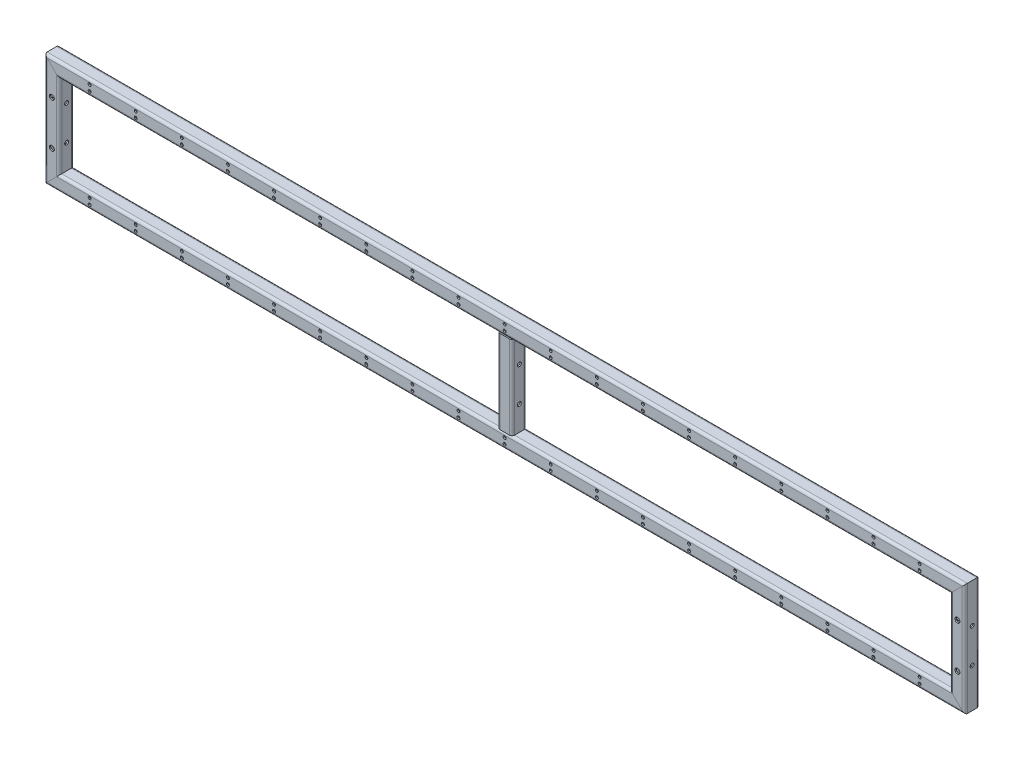
SolidWorks part; units mm, degrees
ref_plane "Front Plane" through (0, 0, 0) normal (0, 0, 1) x (1, 0, 0)
ref_plane "Top Plane" through (0, 0, 0) normal (0, 1, 0) x (1, 0, 0)
ref_plane "Right Plane" through (0, 0, 0) normal (1, 0, 0) x (0, 0, -1)
sketch "Sketch1" plane through (0, 0, 0) normal (0, 0, 1) x (1, 0, 0)
  line L0 (-1876, 15) -> (-1876, -10) construction
  line L1 (-15, -200) -> (-1861, -200)
  line L2 (-15, -200) -> (-15, -400)
  line L3 (-15, -400) -> (-1861, -400)
  line L4 (-1861, -200) -> (-1861, -400)
  line L6 (-938, -200) -> (-938, -400)
  line L7 (-37, -300) -> (-1897.553, -300) construction
  line L8 (-37, -589) -> (-37, -11) construction
  dimension "D1" = 15
  dimension "D2" = 15
  dimension "D3" = 200
  dimension "D4" = 100
other "Structural Member1"
ref_plane "Plane1" through (-1861, -200, 0) normal (0, -1, 0) x (1, 0, 0)
sketch "Sketch11" plane through (-1861, -200, 0) normal (0, -1, 0) x (1, 0, 0)
  line L0 (-9.8, -12.4) -> (9.8, -12.4)
  line L1 (-12.4, -9.8) -> (-12.4, 9.8)
  line L2 (9.8, 12.4) -> (-9.8, 12.4)
  line L3 (12.4, 9.8) -> (12.4, -9.8)
  line L4 (-9.8, -15) -> (9.8, -15)
  line L5 (-15, -9.8) -> (-15, 9.8)
  line L6 (9.8, 15) -> (-9.8, 15)
  line L7 (15, 9.8) -> (15, -9.8)
  arc A0 (15, 9.8) -> (9.8, 15) centre (9.8, 9.8) ccw
  arc A1 (9.8, -15) -> (15, -9.8) centre (9.8, -9.8) ccw
  arc A2 (-15, -9.8) -> (-9.8, -15) centre (-9.8, -9.8) ccw
  arc A3 (-9.8, 15) -> (-15, 9.8) centre (-9.8, 9.8) ccw
  arc A4 (-9.8, 12.4) -> (-12.4, 9.8) centre (-9.8, 9.8) ccw
  arc A5 (12.4, 9.8) -> (9.8, 12.4) centre (9.8, 9.8) ccw
  arc A6 (9.8, -12.4) -> (12.4, -9.8) centre (9.8, -9.8) ccw
  arc A7 (-12.4, -9.8) -> (-9.8, -12.4) centre (-9.8, -9.8) ccw
  point P0 (-15, 0)
  point P1 (15, 0)
  point P2 (0, 15)
  point P3 (0, -15)
  point P4 (0, 0)
  point P5 (-15, -15)
  point P6 (15, -15)
  point P7 (15, 15)
  point P8 (-15, 15)
  point P33 (0, 0)
  dimension "D1" = 5.2
  dimension "Thickness" = 2.6
  dimension "V_leg" = 30
other "Structural Member2"
ref_plane "Plane2" through (-938, -200, 0) normal (0, -1, 0) x (1, 0, 0)
sketch "Sketch12" plane through (-938, -200, 0) normal (0, -1, 0) x (1, 0, 0)
  line L0 (-9.8, -12.4) -> (9.8, -12.4)
  line L1 (-12.4, -9.8) -> (-12.4, 9.8)
  line L2 (9.8, 12.4) -> (-9.8, 12.4)
  line L3 (12.4, 9.8) -> (12.4, -9.8)
  line L4 (-9.8, -15) -> (9.8, -15)
  line L5 (-15, -9.8) -> (-15, 9.8)
  line L6 (9.8, 15) -> (-9.8, 15)
  line L7 (15, 9.8) -> (15, -9.8)
  arc A0 (15, 9.8) -> (9.8, 15) centre (9.8, 9.8) ccw
  arc A1 (9.8, -15) -> (15, -9.8) centre (9.8, -9.8) ccw
  arc A2 (-15, -9.8) -> (-9.8, -15) centre (-9.8, -9.8) ccw
  arc A3 (-9.8, 15) -> (-15, 9.8) centre (-9.8, 9.8) ccw
  arc A4 (-9.8, 12.4) -> (-12.4, 9.8) centre (-9.8, 9.8) ccw
  arc A5 (12.4, 9.8) -> (9.8, 12.4) centre (9.8, 9.8) ccw
  arc A6 (9.8, -12.4) -> (12.4, -9.8) centre (9.8, -9.8) ccw
  arc A7 (-12.4, -9.8) -> (-9.8, -12.4) centre (-9.8, -9.8) ccw
  point P0 (-15, 0)
  point P1 (15, 0)
  point P2 (0, 15)
  point P3 (0, -15)
  point P4 (0, 0)
  point P5 (-15, -15)
  point P6 (15, -15)
  point P7 (15, 15)
  point P8 (-15, 15)
  point P33 (0, 0)
  dimension "D1" = 5.2
  dimension "Thickness" = 2.6
  dimension "V_leg" = 30
other "Trim/Extend1"
sketch "Sketch13" plane through (0, 0, 15) normal (0, 0, 1) x (1, 0, 0)
  circle A0 centre (-92, -194) radius 3
  circle A1 centre (-92, -206) radius 3
  circle A2 centre (-92, -406) radius 3
  circle A3 centre (-92, -394) radius 3.0019
  dimension "D1" = 6
  dimension "D2" = 6
extrude "Cut-Extrude1" cut sketch "Sketch13" against normal through all
pattern_linear "LPattern1" count 19 spacing 94 along (-1, 0, 0) of "Cut-Extrude1"
sketch "Sketch15" plane through (0, 0, -15) normal (0, 0, -1) x (-1, 0, 0)
  circle A0 centre (15, -255) radius 5
  circle A1 centre (15, -345) radius 5
extrude "Cut-Extrude2" cut sketch "Sketch15" against normal through all
sketch "Sketch16" plane through (0, 0, -15) normal (0, 0, -1) x (-1, 0, 0)
  line L0 (938, -200) -> (938, -400) construction
ref_plane "Plane3" through (-938, 0, 0) normal (1, 0, 0) x (0, 0, -1)
mirror "Mirror1" about plane through (-938, 0, 0) normal (1, 0, 0) of "Cut-Extrude2"
sketch "Sketch17" plane through (0, 0, 0) normal (1, 0, 0) x (0, 0, -1)
  line L0 (25, -300) -> (-40.0143, -300) construction
  line L1 (25, -240) -> (25, -360) construction
  line L2 (0, -356.6687) -> (0, -228.7112) construction
  line L3 (0, -200) -> (0, -400) construction
  circle A0 centre (0, -265) radius 4
  circle A1 centre (0, -335) radius 4
  dimension "D1" = 8
  dimension "D2" = 8
  dimension "D3" = 35
  dimension "D4" = 35
extrude "Cut-Extrude3" cut sketch "Sketch17" against normal through all
